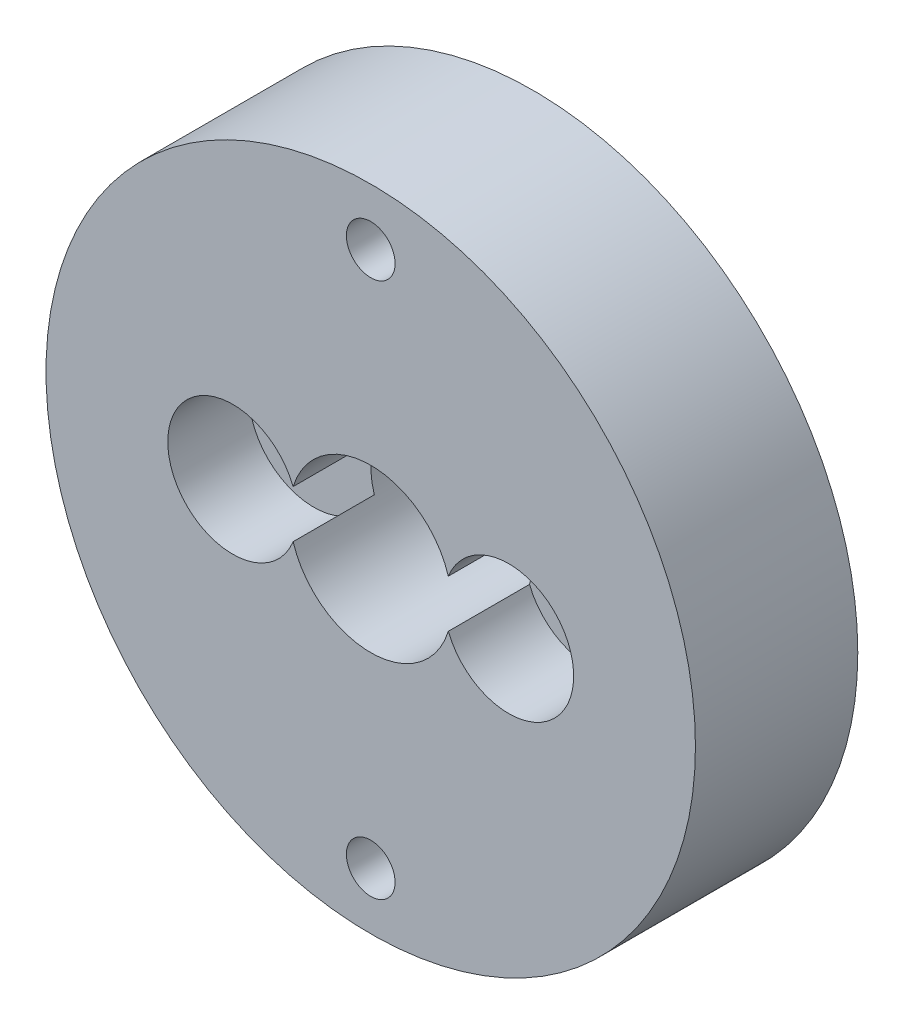
SolidWorks part; units mm, degrees
ref_plane "Front Plane" through (0, 0, 0) normal (0, 0, 1) x (1, 0, 0)
ref_plane "Top Plane" through (0, 0, 0) normal (0, 1, 0) x (1, 0, 0)
ref_plane "Right Plane" through (0, 0, 0) normal (1, 0, 0) x (0, 0, -1)
sketch "Sketch1" plane through (0, 0, 0) normal (0, 0, 1) x (1, 0, 0)
  line L0 (-8.5, 0) -> (8.5, 0) construction
  line L1 (0, 20) -> (0, -20) construction
  line L2 (0, -20) -> (1.4345, -16.0614)
  circle A0 centre (0, 0) radius 20
  circle A1 centre (-8.5, 0) radius 1.25
  circle A2 centre (8.5, 0) radius 1.25
  circle A3 centre (0, 0) radius 5
  circle A4 centre (0, 16.5) radius 1.5
  circle A5 centre (0, -16.5) radius 1.5
  point P5 (0, 0)
  dimension "D2" = 2.5
  dimension "D4" = 2.5
  dimension "D3" = 40
  dimension "D5" = 10
  dimension "D6" = 3
  dimension "D7" = 3
  dimension "D1" = 17
  dimension "D8" = 3.5
  dimension "D9" = 3.5
extrude "Boss-Extrude1" add sketch "Sketch1" along normal blind 10
sketch "Sketch2" plane through (0, 0, 10) normal (0, 0, 1) x (1, 0, 0)
  circle A0 centre (8.5, 0) radius 4
  circle A1 centre (-8.5, 0) radius 4
  dimension "D1" = 8
  dimension "D2" = 8
extrude "Cut-Extrude1" cut sketch "Sketch2" against normal blind 5
